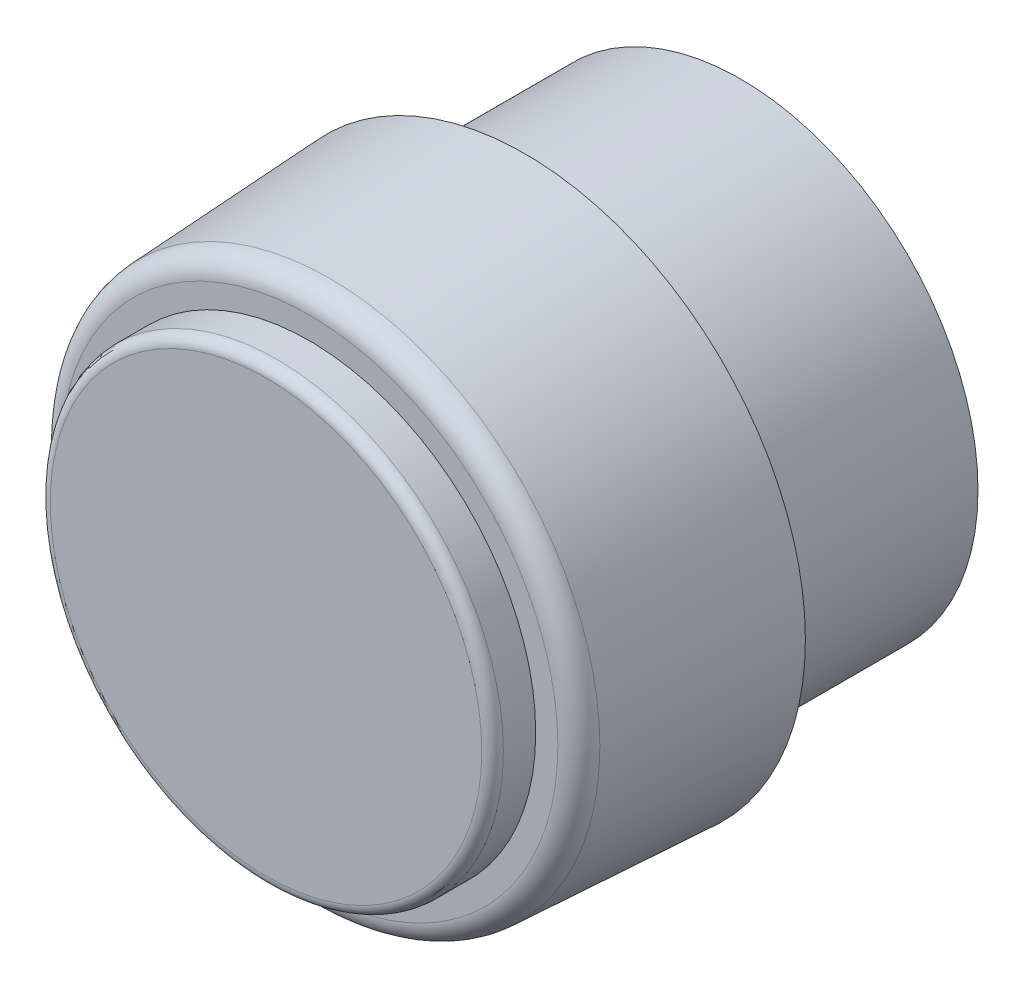
SolidWorks part; units mm, degrees
material "SKD11淬火HRC56－60"
ref_plane "前基準面" through (0, 0, 0) normal (0, 0, 1) x (1, 0, 0)
ref_plane "上基準面" through (0, 0, 0) normal (0, 1, 0) x (1, 0, 0)
ref_plane "右基準面" through (0, 0, 0) normal (1, 0, 0) x (0, 0, -1)
sketch "草图1" plane through (0, 0, 0) normal (0, 0, 1) x (1, 0, 0)
  circle A0 centre (0, 0) radius 11
  dimension "D1" = 22
extrude "凸台-拉伸1" add sketch "草图1" along normal blind 10
sketch "草图2" plane through (0, 0, 10) normal (0, 0, 1) x (1, 0, 0)
  circle A0 centre (0, 0) radius 13
  dimension "D1" = 26
extrude "凸台-拉伸2" add sketch "草图2" along normal blind 10 draft 3
fillet "圆角1" radius 1 1 edges at (12.4759, 0, 20)
sketch "草图3" plane through (0, 0, 20) normal (0, 0, 1) x (1, 0, 0)
  circle A0 centre (0, 0) radius 10.5
  dimension "D1" = 21
extrude "凸台-拉伸3" add sketch "草图3" along normal blind 2
fillet "圆角2" radius 0.5 1 edges at (10.5, 0, 22)
